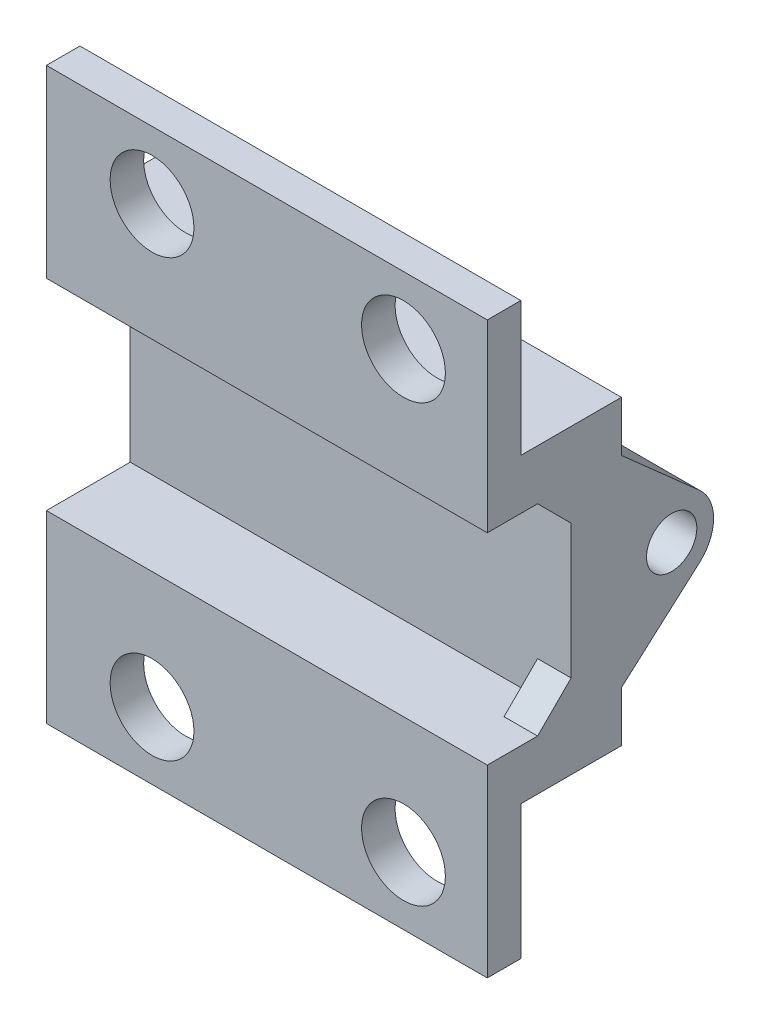
SolidWorks part; units mm, degrees
ref_plane "Front" through (0, 0, 0) normal (0, 0, 1) x (1, 0, 0)
ref_plane "Top" through (0, 0, 0) normal (0, 1, 0) x (1, 0, 0)
ref_plane "Right" through (0, 0, 0) normal (1, 0, 0) x (0, 0, -1)
sketch "Эскиз1" plane through (0, 0, 0) normal (0, 0, 1) x (1, 0, 0)
  line L1 (-12.15, 6) -> (12.15, 6)
  line L2 (-12.15, 6) -> (-12.15, -6)
  line L3 (-12.15, -6) -> (12.15, -6)
  line L4 (12.15, 6) -> (12.15, -6)
  line L5 (-12.15, 6) -> (12.15, -6) construction
  line L6 (-12.15, -6) -> (12.15, 6) construction
  line L7 (-12.15, 9) -> (12.15, 9)
  line L8 (-12.15, 9) -> (-12.15, -9)
  line L9 (-12.15, -9) -> (12.15, -9)
  line L10 (12.15, 9) -> (12.15, -9)
  line L11 (-12.15, 9) -> (12.15, -9) construction
  line L12 (-12.15, -9) -> (12.15, 9) construction
  point P0 (0, 0)
  point P6 (0, 0)
  dimension "D1" = 12
  dimension "D2" = 18
  dimension "D3" = 24.3
extrude "Бобышка-Вытянуть1" add sketch "Эскиз1" along normal blind 5 contours L10 L7 L8 L1 | L10 L3 L8 L9
sketch "Эскиз2" plane through (0, 0, 0) normal (0, 0, -1) x (-1, 0, 0)
  line L1 (-12.15, 9) -> (12.15, 9)
  line L2 (-12.15, 9) -> (-12.15, -9)
  line L3 (-12.15, -9) -> (12.15, -9)
  line L4 (12.15, 9) -> (12.15, -9)
extrude "Бобышка-Вытянуть2" add sketch "Эскиз2" along normal blind 3 separate body
sketch "Эскиз3" plane through (12.15, 0, 0) normal (1, 0, 0) x (0, 0, -1)
  line L0 (-5, 6) -> (-5, 9)
  line L1 (-5, 9) -> (3, 9)
  line L2 (3, 9) -> (3, -9)
  line L3 (3, -9) -> (-5, -9)
  line L4 (-5, -9) -> (-5, -6)
  line L5 (-10, -6) -> (0, -6) construction
  line L6 (-5, -6) -> (-2, -6)
  line L7 (-5, -6) -> (0, -6) construction
  line L8 (-2, -6) -> (0, -4)
  line L9 (0, 9) -> (0, -9) construction
  line L10 (0, -4) -> (0, 4)
  line L11 (0, 4) -> (-2, 6)
  line L12 (-10, 6) -> (0, 6) construction
  line L13 (-2, 6) -> (-5, 6)
  line L14 (-5, 6) -> (0, 6) construction
  line L15 (-5, 9) -> (0, 9) construction
  line L17 (-5, 9) -> (-5, 6) construction
  dimension "D1" = 2
  dimension "D2" = 2
  dimension "D3" = 2
  dimension "D4" = 2
extrude "Бобышка-Вытянуть3" add sketch "Эскиз3" along normal blind 2
sketch "Эскиз6" plane through (14.15, 0, 0) normal (1, 0, 0) x (0, 0, -1)
  line L0 (3, 6) -> (7.6583, 1.8708)
  line L1 (3, -9) -> (3, 9) construction
  line L2 (3, -6) -> (7.6583, -1.8708)
  line L3 (0, 0) -> (11.9434, 0) construction
  line L4 (3, 6) -> (3, -6)
  circle A0 centre (6, 0) radius 1.5
  circle A1 centre (6, 0) radius 2.5
  line M11 (3, -9) -> (3, 9)
  dimension "D1" = 3
  dimension "D2" = 5
  dimension "D3" = 3
  dimension "D4" = 12
extrude "Бобышка-Вытянуть5" add sketch "Эскиз6" against normal blind 6 contours L4 L3 A1 L0 | A1 L3 A0 | L3 A1 A0 | L3 L2 A1 M11
sketch "Эскиз7" plane through (14.15, 0, 0) normal (1, 0, 0) x (0, 0, -1)
  line L1 (-5, 9) -> (-3, 9)
  line L2 (-5, 9) -> (-5, 17)
  line L3 (-5, 17) -> (-3, 17)
  line L4 (-3, 9) -> (-3, 17)
  line L5 (-5, -9) -> (-3, -9)
  line L6 (-5, -9) -> (-5, -17)
  line L7 (-5, -17) -> (-3, -17)
  line L8 (-3, -9) -> (-3, -17)
  dimension "D1" = 2
  dimension "D2" = 8
extrude "Бобышка-Вытянуть6" add sketch "Эскиз7" against normal up to surface (26.3 mm away) up to face at (-12.15, 0, 1.75)
sketch "Эскиз8" plane through (0, 0, 3) normal (0, 0, -1) x (-1, 0, 0)
  line L0 (-14.15, 9) -> (-14.15, 17) construction
  line L1 (12.15, 17) -> (-14.15, 17) construction
  line L2 (0, 0) -> (11.5677, 0) construction
  circle A0 centre (5.85, -13) radius 2.5
  circle A1 centre (-9.15, -13) radius 2.5
  circle A2 centre (-9.15, 13) radius 2.5
  circle A3 centre (5.85, 13) radius 2.5
  dimension "D1" = 5
  dimension "D2" = 5
  dimension "D3" = 4
  dimension "D4" = 15
extrude "Вырез-Вытянуть2" cut sketch "Эскиз8" against normal up to surface (2 mm away) up to face at (1, 11.5, 5)
